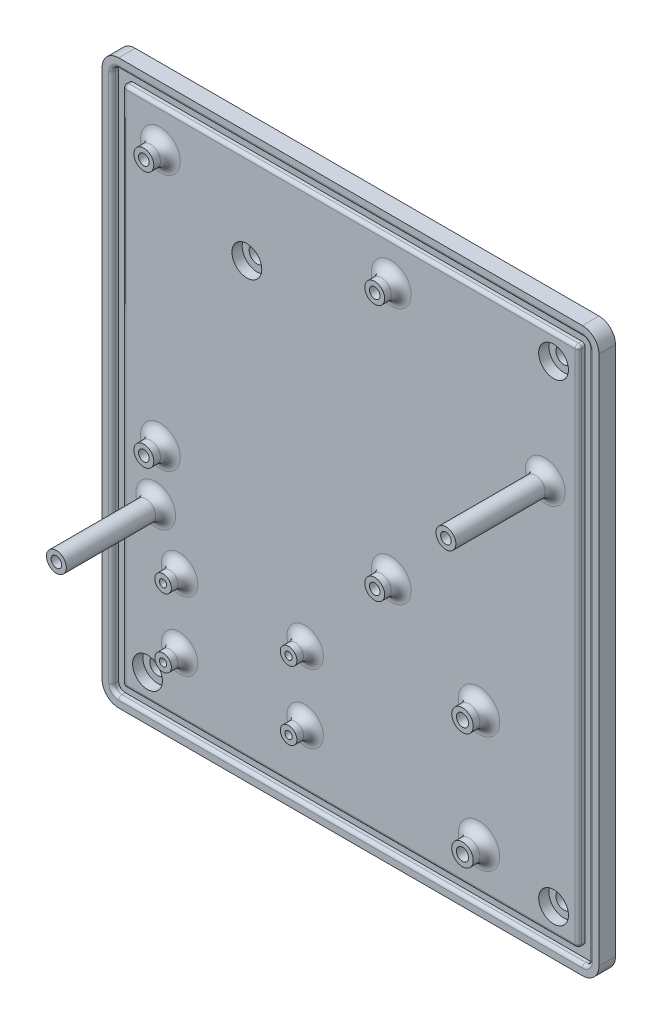
SolidWorks part; units mm, degrees
ref_plane "Plano frontal" through (0, 0, 0) normal (0, 0, 1) x (1, 0, 0)
ref_plane "Plano superior" through (0, 0, 0) normal (0, 1, 0) x (1, 0, 0)
ref_plane "Plano direito" through (0, 0, 0) normal (1, 0, 0) x (0, 0, -1)
sketch "Esboço1" plane through (0, 0, 0) normal (0, 0, 1) x (1, 0, 0)
  line L1 (0, -5) -> (140, -5)
  line L2 (-5, 0) -> (-5, 160)
  line L3 (0, 165) -> (140, 165)
  line L4 (145, 0) -> (145, 160)
  arc A0 (-5, 0) -> (0, -5) centre (0, 0) ccw
  arc A1 (0, 165) -> (-5, 160) centre (0, 160) ccw
  arc A2 (145, 160) -> (140, 165) centre (140, 160) ccw
  arc A3 (140, -5) -> (145, 0) centre (140, 0) ccw
  dimension "D3" = 10
  dimension "D1" = 170
  dimension "D2" = 150
extrude "Ressalto-extrusão1" add sketch "Esboço1" along normal blind 5
sketch "Esboço5" plane through (0, 0, 5) normal (0, 0, 1) x (1, 0, 0)
  line L4 (138.8, 1.2) -> (138.8, 158.8)
  line L5 (138.8, 158.8) -> (1.2, 158.8)
  line L6 (1.2, 158.8) -> (1.2, 1.2)
  line L7 (1.2, 1.2) -> (138.8, 1.2)
  line L8 (142, 0) -> (142, 160)
  line L9 (140, 162) -> (0, 162)
  line L10 (-2, 160) -> (-2, 0)
  line L11 (0, -2) -> (140, -2)
  line L12 (142, 0) -> (142, 160)
  line L13 (140, 162) -> (0, 162)
  line L14 (-2, 160) -> (-2, 0)
  line L15 (0, -2) -> (140, -2)
  arc A4 (138.8, 158.8) -> (138.8, 158.8) centre (138.8, 158.8) ccw
  arc A5 (1.2, 158.8) -> (1.2, 158.8) centre (1.2, 158.8) ccw
  arc A6 (1.2, 1.2) -> (1.2, 1.2) centre (1.2, 1.2) ccw
  arc A7 (138.8, 1.2) -> (138.8, 1.2) centre (138.8, 1.2) ccw
  arc A8 (140, -2) -> (142, 0) centre (140, 0) ccw
  arc A9 (142, 160) -> (140, 162) centre (140, 160) ccw
  arc A10 (0, 162) -> (-2, 160) centre (0, 160) ccw
  arc A11 (-2, 0) -> (0, -2) centre (0, 0) ccw
  arc A12 (140, -2) -> (142, 0) centre (140, 0) ccw
  arc A13 (142, 160) -> (140, 162) centre (140, 160) ccw
  arc A14 (0, 162) -> (-2, 160) centre (0, 160) ccw
  arc A15 (-2, 0) -> (0, -2) centre (0, 0) ccw
  dimension "D1" = 3
  dimension "D2" = 3.2
extrude "Corte-extrusão1" cut sketch "Esboço5" against normal blind 2
fillet "Filete2" radius 1 8 edges at (142, 80, 5) (141.4142, 161.4142, 5) (70, 162, 5) (-1.4142, 161.4142, 5) (-2, 80, 5) (-1.4142, -1.4142, 5) (70, -2, 5) (141.4142, -1.4142, 5)
fillet "Filete4" radius 1 4 edges at (1.2, 158.8, 4) (138.8, 158.8, 4) (138.8, 1.2, 4) (1.2, 1.2, 4)
sketch "Esboço6" plane through (0, 0, 5) normal (0, 0, 1) x (1, 0, 0)
  line L0 (108.8, 31.2) -> (140.7554, 31.2) construction
  line L1 (6.2, 153.8) -> (89.2, 153.8) construction
  line L2 (6.2, 153.8) -> (6.2, 61.8) construction
  line L3 (6.2, 61.8) -> (89.2, 61.8) construction
  line L4 (89.2, 153.8) -> (89.2, 61.8) construction
  line L5 (16.2, 16.2) -> (58.5, 16.2) construction
  line L6 (16.2, 16.2) -> (16.2, 41.7) construction
  line L7 (16.2, 41.7) -> (58.5, 41.7) construction
  line L8 (58.5, 16.2) -> (58.5, 41.7) construction
  line L9 (108.8, 31.2) -> (108.8, 53.25) construction
  line L10 (37.35, 16.2) -> (37.35, 41.7) construction
  line L11 (37.35, 28.95) -> (58.5, 28.95) construction
  line L12 (137.8, 158.8) -> (2.2, 158.8) construction
  line L13 (1.2, 157.8) -> (1.2, 2.2) construction
  line L15 (2.2, 1.2) -> (137.8, 1.2) construction
  line L18 (138.8, 2.2) -> (138.8, 157.8) construction
  circle A0 centre (108.8, 31.2) radius 22.05 construction
  circle A1 centre (12.6, 147.2) radius 3
  circle A2 centre (82.3, 147.2) radius 3
  circle A3 centre (82.3, 69.8) radius 3
  circle A4 centre (12.6, 69.8) radius 3
  circle A5 centre (108.8, 48.75) radius 3.25
  circle A6 centre (108.8, 13.65) radius 3.25
  circle A7 centre (56.3, 18.6) radius 2.5
  circle A8 centre (18.4, 39.3) radius 2.5
  circle A9 centre (18.4, 18.6) radius 2.5
  circle A10 centre (56.3, 39.3) radius 2.5
  dimension "D3" = 44.1
  dimension "D10" = 4.5
  dimension "D11" = 6.5
  dimension "D12" = 6
  dimension "D13" = 5
  dimension "D16" = 5
  dimension "D1" = 83
  dimension "D2" = 92
  dimension "D4" = 42.3
  dimension "D5" = 25.5
  dimension "D6" = 6.4
  dimension "D7" = 6.6
  dimension "D8" = 77.4
  dimension "D9" = 69.7
  dimension "D14" = 2.4
  dimension "D15" = 2.2
  dimension "D17" = 5
  dimension "D18" = 30
  dimension "D19" = 30
  dimension "D20" = 15
  dimension "D21" = 15
extrude "Ressalto-extrusão3" add sketch "Esboço6" along normal blind 5
sketch "Esboço18" plane through (0, 0, 5) normal (0, 0, 1) x (1, 0, 0)
  line L0 (137.8, 158.8) -> (2.2, 158.8) construction
  line L1 (1.2, 157.8) -> (1.2, 2.2) construction
  line L2 (138.8, 2.2) -> (138.8, 157.8) construction
  circle A0 centre (128.8, 118.8) radius 3
  circle A1 centre (11.2, 53.8) radius 3
  dimension "D5" = 6
  dimension "D1" = 105
  dimension "D2" = 10
  dimension "D3" = 10
  dimension "D4" = 40
extrude "Ressalto-extrusão4" add sketch "Esboço18" along normal blind 30
fillet "Filete5" radius 3 12 edges at (112.05, 13.65, 5) (112.05, 48.75, 5) (53.8, 18.6, 5) (58.8, 39.3, 5) (20.9, 18.6, 5) (15.9, 39.3, 5) (85.3, 69.8, 5) (15.6, 69.8, 5) (85.3, 147.2, 5) (15.6, 147.2, 5) (131.8, 118.8, 5) (14.2, 53.8, 5)
hole_wizard "Furo com folga de M3.51" positions "Esboço8" profile "Esboço7" hole size "M3.5" standard "ISO" end condition through all
sketch "Esboço8" plane through (0, 0, 10) normal (0, 0, 1) x (1, 0, 0)
  point P0 (108.8, 13.65)
  point P3 (108.8, 48.75)
sketch "Esboço7" plane through (108.8, 13.65, 10) normal (1, 0, 0) x (0, -1, 0)
  line L0 (0, 0) -> (0, 10)
  line L1 (0, 10) -> (1.85, 10)
  line L2 (1.85, 10) -> (1.85, 0)
  line L5 (1.85, 0) -> (0, 0)
  line L11 (0, -6.35) -> (0, 107.95) construction
  dimension "Thru Hole Dia." = 3.7
  dimension "Thru Hole Depth" = 10
hole_wizard "Furo com folga de M21" positions "Esboço10" profile "Esboço9" hole size "M2" standard "ISO" end condition through all
sketch "Esboço10" plane through (0, 0, 10) normal (0, 0, 1) x (1, 0, 0)
  point P0 (18.4, 39.3)
  point P3 (18.4, 18.6)
  point P6 (56.3, 39.3)
  point P9 (56.3, 18.6)
sketch "Esboço9" plane through (18.4, 39.3, 10) normal (1, 0, 0) x (0, -1, 0)
  line L0 (0, 0) -> (0, 10)
  line L1 (0, 10) -> (1.1, 10)
  line L2 (1.1, 10) -> (1.1, 0)
  line L5 (1.1, 0) -> (0, 0)
  line L11 (0, -6.35) -> (0, 107.95) construction
  dimension "Thru Hole Dia." = 2.2
  dimension "Thru Hole Depth" = 10
hole_wizard "Furo com folga de M31" positions "Esboço12" profile "Esboço11" hole size "M3" standard "ISO" end condition through all
sketch "Esboço12" plane through (0, 0, 10) normal (0, 0, 1) x (1, 0, 0)
  point P0 (12.6, 147.2)
  point P3 (82.3, 147.2)
  point P6 (82.3, 69.8)
  point P9 (12.6, 69.8)
sketch "Esboço11" plane through (12.6, 147.2, 10) normal (1, 0, 0) x (0, -1, 0)
  line L0 (0, 0) -> (0, 10)
  line L1 (0, 10) -> (1.6, 10)
  line L2 (1.6, 10) -> (1.6, 0)
  line L5 (1.6, 0) -> (0, 0)
  line L11 (0, -6.35) -> (0, 107.95) construction
  dimension "Thru Hole Dia." = 3.2
  dimension "Thru Hole Depth" = 10
sketch "Esboço13" plane through (0, 0, 5) normal (0, 0, 1) x (1, 0, 0)
  line L0 (138.8, 2.2) -> (138.8, 157.8) construction
  line L1 (8.7, 8.7) -> (131.3, 8.7) construction
  line L2 (8.7, 8.7) -> (8.7, 151.3) construction
  line L3 (8.7, 151.3) -> (131.3, 151.3) construction
  line L4 (131.3, 8.7) -> (131.3, 151.3) construction
  line L5 (2.2, 1.2) -> (137.8, 1.2) construction
  line L6 (1.2, 157.8) -> (1.2, 2.2) construction
  line L7 (137.8, 158.8) -> (2.2, 158.8) construction
  line L9 (8.7, 151.3) -> (38.7, 151.3) construction
  line L10 (8.7, 151.3) -> (8.7, 131.3) construction
  line L11 (8.7, 131.3) -> (38.7, 131.3) construction
  line L12 (38.7, 151.3) -> (38.7, 131.3) construction
  dimension "D1" = 7.5
  dimension "D2" = 7.5
  dimension "D3" = 7.5
  dimension "D4" = 7.5
  dimension "D5" = 30
  dimension "D6" = 20
hole_wizard "Rebaixo para parafuso com cabeça panela de M41" positions "Esboço15" profile "Esboço14" counterbore size "M4" standard "ISO" end condition through all
sketch "Esboço15" plane through (0, 0, 5) normal (0, 0, 1) x (1, 0, 0)
  point P0 (38.7, 131.3)
  point P3 (131.3, 151.3)
  point P6 (131.3, 8.7)
  point P9 (8.7, 8.7)
sketch "Esboço14" plane through (38.7, 131.3, 5) normal (1, 0, 0) x (0, -1, 0)
  line L0 (0, 0) -> (0, 5)
  line L1 (0, 5) -> (2.4, 5)
  line L3 (2.4, 5) -> (2.4, 3.1)
  line L4 (2.4, 3.1) -> (4.5, 3.1)
  line L5 (4.5, 3.1) -> (4.5, 0)
  line L7 (4.5, 0) -> (0, 0)
  line L11 (0, -6.35) -> (0, 107.95) construction
  dimension "Thru Hole Dia." = 4.8
  dimension "Thru Hole Depth" = 5
  dimension "C'Bore Dia." = 9
  dimension "C'Bore Depth" = 3.1
fillet "Filete6" radius 1 8 edges at (138.5071, 1.4929, 5) (70, 1.2, 5) (1.4929, 1.4929, 5) (1.2, 80, 5) (1.4929, 158.5071, 5) (70, 158.8, 5) (138.5071, 158.5071, 5) (138.8, 80, 5)
hole_wizard "Furo com folga de M32" positions "Esboço20" profile "Esboço19" hole size "M3" standard "ISO"
sketch "Esboço20" plane through (0, 0, 35) normal (0, 0, 1) x (1, 0, 0)
  point P1 (128.8, 118.8)
  point P4 (11.2, 53.8)
sketch "Esboço19" plane through (128.8, 118.8, 35) normal (1, 0, 0) x (0, -1, 0)
  line L0 (0, 0) -> (0, 15.9614)
  line L1 (0, 15.9614) -> (1.6, 15)
  line L2 (1.6, 15) -> (1.6, 0)
  line L5 (1.6, 0) -> (0, 0)
  line L10 (0, 15.9614) -> (-1.6, 15) construction
  line L11 (0, -6.35) -> (0, 107.95) construction
  dimension "Hole Dia." = 3.2
  dimension "Hole Depth" = 15
  dimension "Drill Angle" = 118
